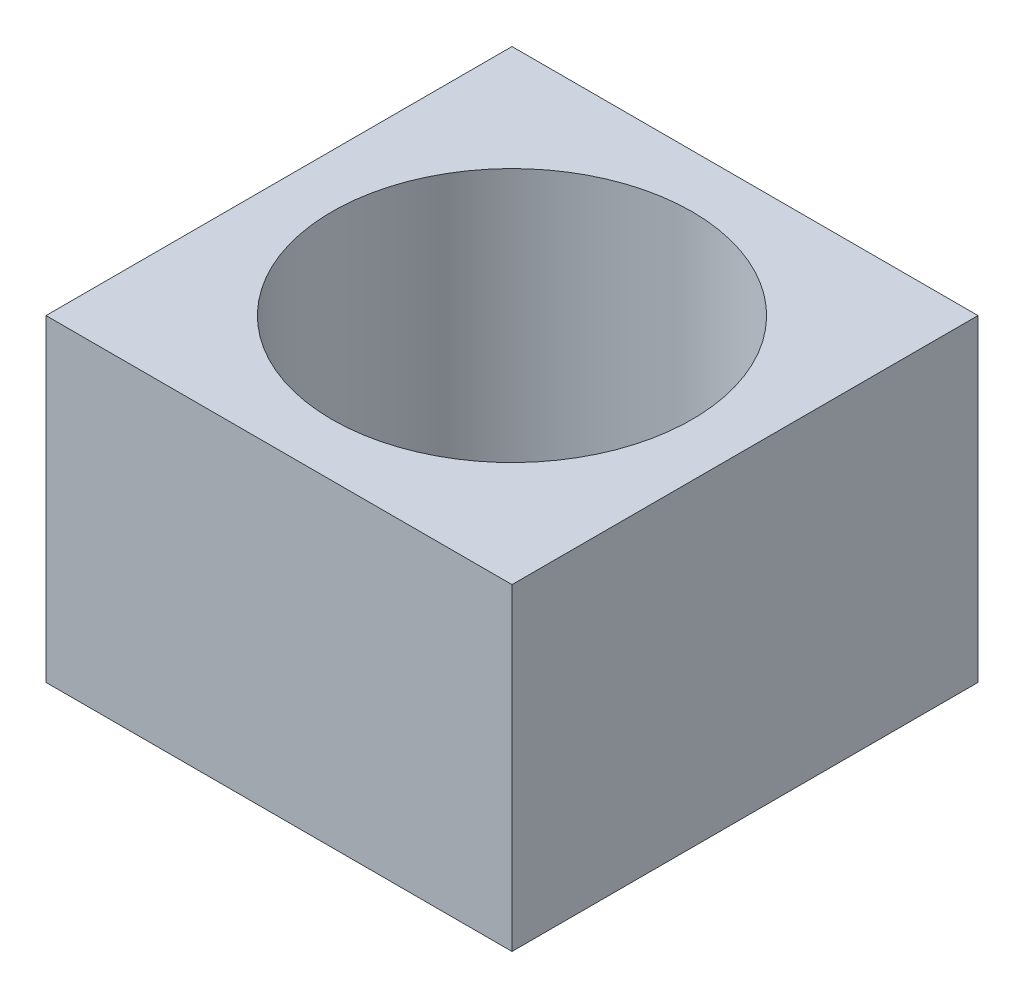
SolidWorks part; units mm, degrees
ref_plane "前视基准面" through (0, 0, 0) normal (0, 0, 1) x (1, 0, 0)
ref_plane "上视基准面" through (0, 0, 0) normal (0, 1, 0) x (1, 0, 0)
ref_plane "右视基准面" through (0, 0, 0) normal (1, 0, 0) x (0, 0, -1)
other "Configuration Table"
sketch "草图1" plane through (0, 0, 0) normal (0, 1, 0) x (1, 0, 0)
  line L9 (-22, 22) -> (22, 22)
  line L10 (-22, 22) -> (-22, -22)
  line L11 (-22, -22) -> (22, -22)
  line L12 (22, 22) -> (22, -22)
  line L13 (0, -22) -> (0, 22) construction
  line L14 (-22, 0) -> (22, 0) construction
  point P0 (0, 0)
extrude "凸台-拉伸1" add sketch "草图1" along normal blind 30 contours L10 L11 L12 L9
sketch "草图2" plane through (0, 0, 0) normal (0, 1, 0) x (1, 0, 0)
  circle A0 centre (0, 0) radius 17
extrude "切除-拉伸1" cut sketch "草图2" along normal blind 30
